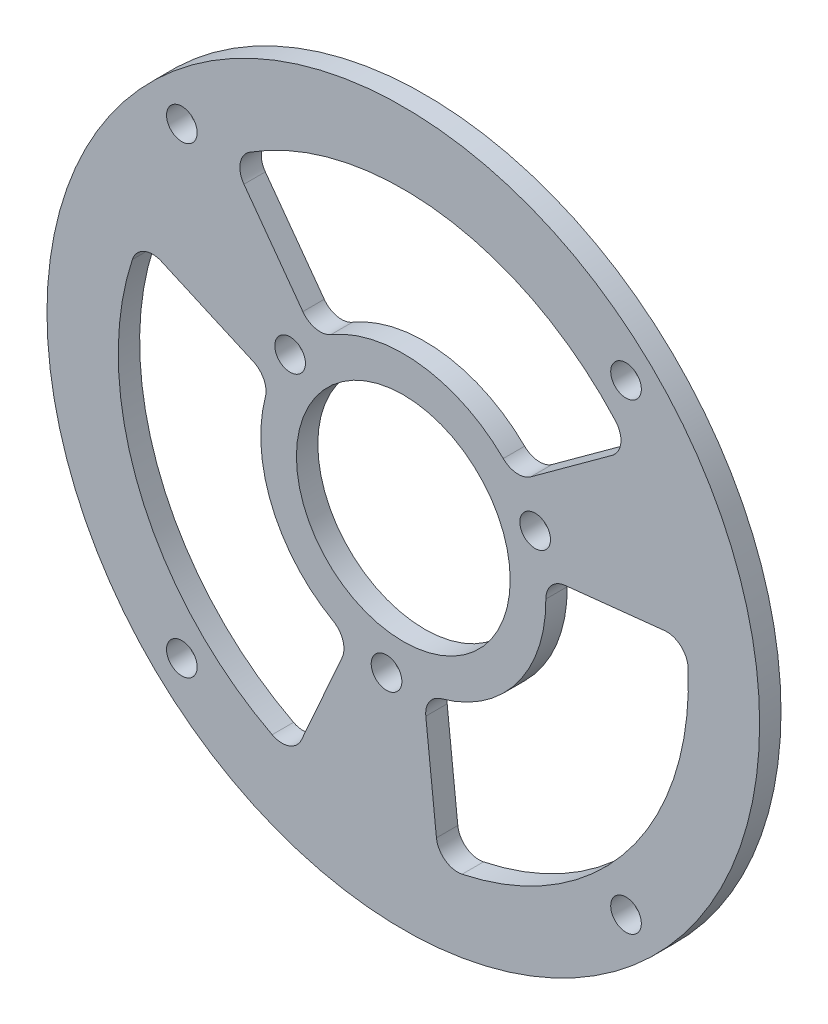
SolidWorks part; units mm, degrees
ref_plane "前视基准面" through (0, 0, 0) normal (0, 0, 1) x (1, 0, 0)
ref_plane "上视基准面" through (0, 0, 0) normal (0, 1, 0) x (1, 0, 0)
ref_plane "右视基准面" through (0, 0, 0) normal (1, 0, 0) x (0, 0, -1)
sketch "草图1" plane through (0, 0, 0) normal (0, 0, 1) x (1, 0, 0)
  circle A0 centre (-43.0467, 46.8167) radius 50
  circle A1 centre (-43.0467, 46.8167) radius 15
  circle A2 centre (-58.9279, 58.7614) radius 2.15
  circle A3 centre (-45.4013, 26.8705) radius 2.15
  circle A4 centre (-24.5463, 54.5304) radius 2.15
  point P9 (0, 0)
  point P10 (-58.9331, 58.8868)
  point P11 (-58.9279, 58.7614)
  point P12 (-58.9279, 58.7614)
  point P13 (-24.5463, 54.5304)
  point P14 (-45.4013, 26.8705)
  dimension "D1" = 100
  dimension "D2" = 4.3
  dimension "D3" = 30
extrude "凸台-拉伸1" add sketch "草图1" along normal blind 3
sketch "草图2" plane through (0, 0, 0) normal (0, 0, -1) x (-1, 0, 0)
  line L1 (11.7957, 14.2572) -> (74.1213, 14.2572) construction
  line L2 (11.7957, 14.2572) -> (11.7957, 79.1843) construction
  line L3 (11.7957, 79.1843) -> (74.1213, 79.1843) construction
  line L4 (74.1213, 14.2572) -> (74.1213, 79.1843) construction
  line L5 (11.7957, 14.2572) -> (74.1213, 79.1843) construction
  line L6 (11.7957, 79.1843) -> (74.1213, 14.2572) construction
  circle A0 centre (42.9585, 46.7208) radius 45 construction
  circle A1 centre (11.7957, 79.1843) radius 2.15
  circle A2 centre (74.1213, 79.1843) radius 2.15
  circle A3 centre (74.1213, 14.2572) radius 2.15
  circle A4 centre (11.7957, 14.2572) radius 2.15
  point P0 (42.9585, 46.7208)
  dimension "D2" = 4.3
  dimension "D3" = 90
extrude "切除-拉伸1" cut sketch "草图2" against normal blind 3
sketch "草图3" plane through (0, 0, 0) normal (0, 0, -1) x (-1, 0, 0)
  line L0 (25.1535, 60.7908) -> (13.7422, 69.1032)
  line L2 (65.4088, 76.2194) -> (57.1414, 64.87)
  line L3 (20.3649, 49.9965) -> (6.4023, 51.4815)
  line L5 (38.3983, 10.295) -> (39.8915, 24.3337)
  line L6 (64.0952, 55.3258) -> (76.9996, 61.052)
  line L8 (57.3291, 12.7493) -> (51.6339, 25.5838)
  arc A0 (3.0881, 48.6347) -> (34.7964, 7.6768) centre (43.0467, 46.8167) ccw
  arc A1 (23.0475, 46.9876) -> (37.709, 27.5422) centre (43.0467, 46.8167) ccw
  arc A2 (53.1944, 64.0512) -> (29.0233, 61.0766) centre (43.0467, 46.8167) ccw
  arc A3 (64.6005, 80.513) -> (13.2757, 73.5317) centre (43.0467, 46.8167) ccw
  arc A4 (52.8984, 29.4114) -> (62.4079, 51.8314) centre (43.0467, 46.8167) ccw
  arc A5 (61.4516, 11.3025) -> (81.068, 59.2417) centre (43.0467, 46.8167) ccw
  arc A6 (34.7964, 7.6768) -> (38.3983, 10.295) centre (35.4152, 10.6123) ccw
  arc A7 (6.4023, 51.4815) -> (3.0881, 48.6347) centre (6.085, 48.4984) ccw
  arc A8 (20.3649, 49.9965) -> (23.0475, 46.9876) centre (20.0476, 47.0133) cw
  arc A9 (39.8915, 24.3337) -> (37.709, 27.5422) centre (36.9084, 24.651) ccw
  arc A10 (61.4516, 11.3025) -> (57.3291, 12.7493) centre (60.0713, 13.9661) cw
  arc A11 (51.6339, 25.5838) -> (52.8984, 29.4114) centre (54.3761, 26.8006) cw
  arc A12 (64.0952, 55.3258) -> (62.4079, 51.8314) centre (65.312, 52.5836) ccw
  arc A13 (76.9996, 61.052) -> (81.068, 59.2417) centre (78.2164, 58.3098) cw
  arc A14 (64.6005, 80.513) -> (65.4088, 76.2194) centre (62.9839, 77.9858) cw
  arc A15 (57.1414, 64.87) -> (53.1944, 64.0512) centre (54.7165, 66.6363) cw
  arc A16 (25.1535, 60.7908) -> (29.0233, 61.0766) centre (26.9198, 63.2156) ccw
  arc A17 (13.7422, 69.1032) -> (13.2757, 73.5317) centre (15.5086, 71.5281) cw
  circle A18 centre (43.0467, 46.8167) radius 50 construction
  point P23 (58.5704, 9.9519)
  point P26 (50.4555, 28.2396)
  point P33 (67.2107, 78.6931)
  point P36 (55.4306, 62.5215)
  dimension "D1" = 80
  dimension "D2" = 40
  dimension "D6" = 3
  dimension "D3" = 30
  dimension "D4" = 30
  dimension "D5" = 30
  dimension "D7" = 90
  dimension "D8" = 90
extrude "切除-拉伸2" cut sketch "草图3" against normal blind 3
